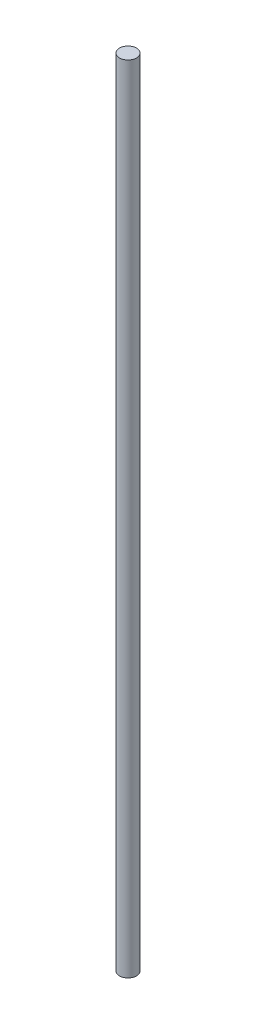
SolidWorks part; units mm, degrees
ref_plane "Front Plane" through (0, 0, 0) normal (0, 0, 1) x (1, 0, 0)
ref_plane "Top Plane" through (0, 0, 0) normal (0, 1, 0) x (1, 0, 0)
ref_plane "Right Plane" through (0, 0, 0) normal (1, 0, 0) x (0, 0, -1)
sketch "Sketch1" plane through (0, 0, 0) normal (0, 1, 0) x (1, 0, 0)
  circle A0 centre (0, 0) radius 1.5
  dimension "D1" = 3
extrude "Boss-Extrude1" add sketch "Sketch1" along normal blind 139
